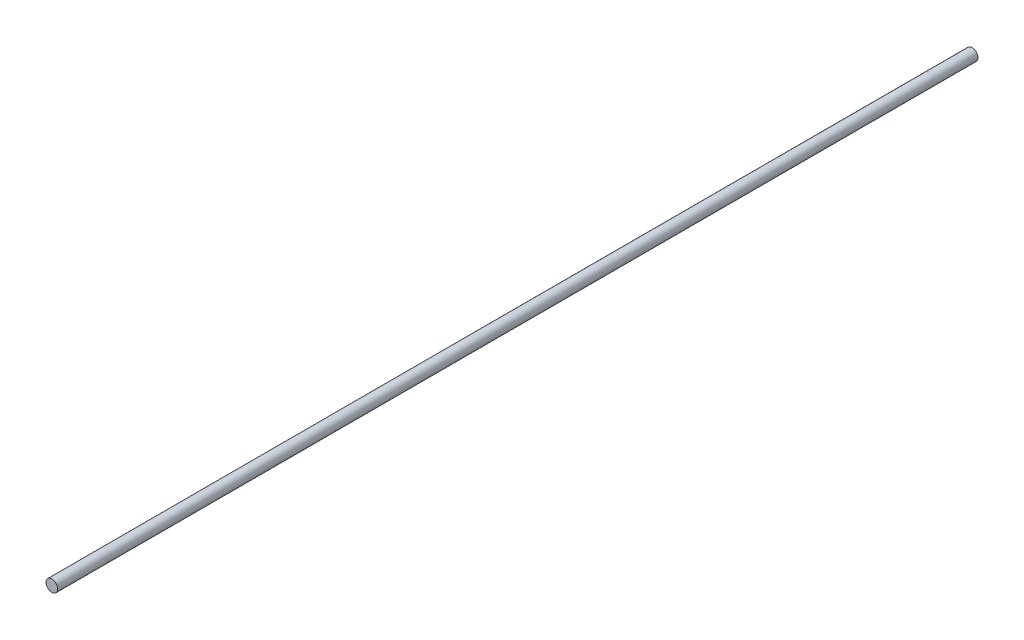
SolidWorks part; units mm, degrees
material "1.4000 (X6Cr13)"
ref_plane "Ebene vorne" through (0, 0, 0) normal (0, 0, 1) x (1, 0, 0)
ref_plane "Ebene oben" through (0, 0, 0) normal (0, 1, 0) x (1, 0, 0)
ref_plane "Ebene rechts" through (0, 0, 0) normal (1, 0, 0) x (0, 0, -1)
sketch "Skizze1" plane through (0, 0, 0) normal (0, 0, 1) x (1, 0, 0)
  circle A0 centre (0, 0) radius 4
extrude "Aufsatz-Linear austragen1" add sketch "Skizze1" along normal blind 630
